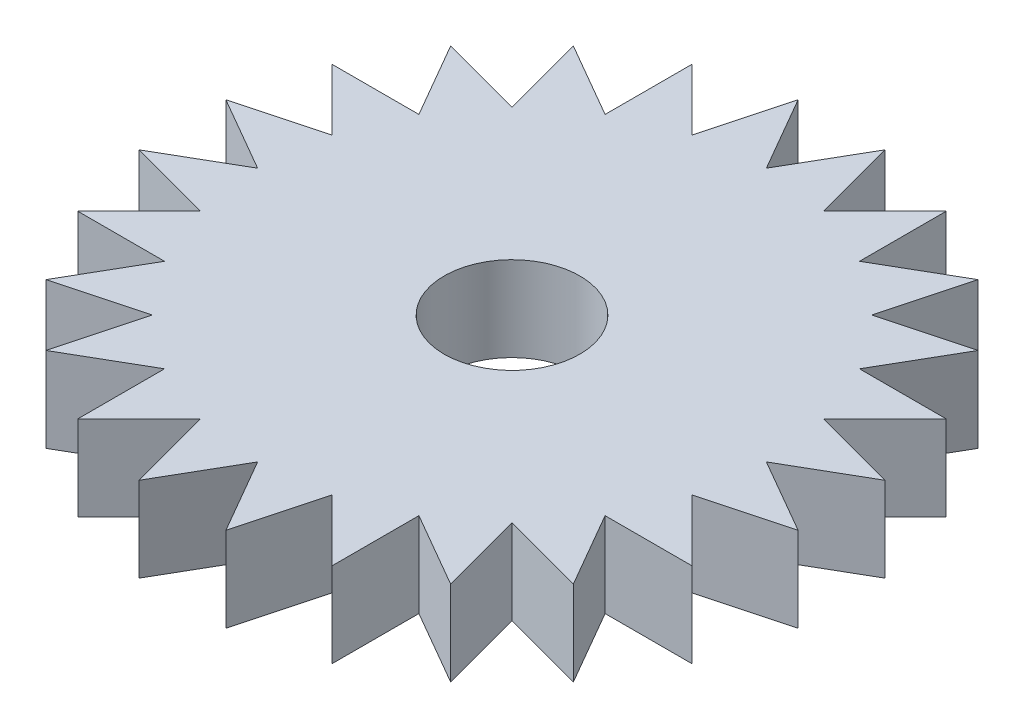
SolidWorks part; units mm, degrees
ref_plane "Front Plane" through (0, 0, 0) normal (0, 0, 1) x (1, 0, 0)
ref_plane "Top Plane" through (0, 0, 0) normal (0, 1, 0) x (1, 0, 0)
ref_plane "Right Plane" through (0, 0, 0) normal (1, 0, 0) x (0, 0, -1)
sketch "Sketch2" plane through (0, 0, 0) normal (0, 1, 0) x (1, 0, 0)
  line L0 (0, 0) -> (16.4978, 9.525) construction
  line L1 (-9.525, 16.4978) -> (9.525, -16.4978) construction
  line L2 (9.525, -16.4978) -> (4.9305, -18.4009)
  line L3 (4.9305, -18.4009) -> (-4.9305, 18.4009) construction
  line L4 (-4.9305, 18.4009) -> (-7.2278, 17.4493)
  line L5 (-9.525, 16.4978) -> (-9.525, 22.9954)
  line L6 (-9.525, 22.9954) -> (-4.9305, 18.4009)
  line L7 (-9.525, 22.9954) -> (0, 0) construction
  line L8 (-9.525, 16.4978) -> (-7.2278, 17.4493)
  line L9 (-13.4704, 13.4704) -> (-11.4977, 14.9841)
  line L10 (-9.525, 16.4978) -> (-11.4977, 14.9841)
  line L11 (-15.1521, 19.7466) -> (-9.525, 16.4978)
  line L12 (-13.4704, 13.4704) -> (-15.1521, 19.7466)
  line L13 (-16.4978, 9.525) -> (-14.9841, 11.4977)
  line L14 (-13.4704, 13.4704) -> (-14.9841, 11.4977)
  line L15 (-19.7466, 15.1521) -> (-13.4704, 13.4704)
  line L16 (-16.4978, 9.525) -> (-19.7466, 15.1521)
  line L17 (-18.4009, 4.9305) -> (-17.4493, 7.2278)
  line L18 (-16.4978, 9.525) -> (-17.4493, 7.2278)
  line L19 (-22.9954, 9.525) -> (-16.4978, 9.525)
  line L20 (-18.4009, 4.9305) -> (-22.9954, 9.525)
  line L21 (-19.05, 0) -> (-18.7254, 2.4653)
  line L22 (-18.4009, 4.9305) -> (-18.7254, 2.4653)
  line L23 (-24.6771, 3.2488) -> (-18.4009, 4.9305)
  line L24 (-19.05, 0) -> (-24.6771, 3.2488)
  line L25 (-18.4009, -4.9305) -> (-18.7254, -2.4653)
  line L26 (-19.05, 0) -> (-18.7254, -2.4653)
  line L27 (-24.6771, -3.2488) -> (-19.05, 0)
  line L28 (-18.4009, -4.9305) -> (-24.6771, -3.2488)
  line L29 (-16.4978, -9.525) -> (-17.4493, -7.2278)
  line L30 (-18.4009, -4.9305) -> (-17.4493, -7.2278)
  line L31 (-22.9954, -9.525) -> (-18.4009, -4.9305)
  line L32 (-16.4978, -9.525) -> (-22.9954, -9.525)
  line L33 (-13.4704, -13.4704) -> (-14.9841, -11.4977)
  line L34 (-16.4978, -9.525) -> (-14.9841, -11.4977)
  line L35 (-19.7466, -15.1521) -> (-16.4978, -9.525)
  line L36 (-13.4704, -13.4704) -> (-19.7466, -15.1521)
  line L37 (-9.525, -16.4978) -> (-11.4977, -14.9841)
  line L38 (-13.4704, -13.4704) -> (-11.4977, -14.9841)
  line L39 (-15.1521, -19.7466) -> (-13.4704, -13.4704)
  line L40 (-9.525, -16.4978) -> (-15.1521, -19.7466)
  line L41 (-4.9305, -18.4009) -> (-7.2278, -17.4493)
  line L42 (-9.525, -16.4978) -> (-7.2278, -17.4493)
  line L43 (-9.525, -22.9954) -> (-9.525, -16.4978)
  line L44 (-4.9305, -18.4009) -> (-9.525, -22.9954)
  line L45 (0, -19.05) -> (-2.4653, -18.7254)
  line L46 (-4.9305, -18.4009) -> (-2.4653, -18.7254)
  line L47 (-3.2488, -24.6771) -> (-4.9305, -18.4009)
  line L48 (0, -19.05) -> (-3.2488, -24.6771)
  line L49 (4.9305, -18.4009) -> (2.4653, -18.7254)
  line L50 (0, -19.05) -> (2.4653, -18.7254)
  line L51 (3.2488, -24.6771) -> (0, -19.05)
  line L52 (4.9305, -18.4009) -> (3.2488, -24.6771)
  line L53 (9.525, -16.4978) -> (7.2278, -17.4493)
  line L54 (4.9305, -18.4009) -> (7.2278, -17.4493)
  line L55 (9.525, -22.9954) -> (4.9305, -18.4009)
  line L56 (9.525, -16.4978) -> (9.525, -22.9954)
  line L57 (13.4704, -13.4704) -> (11.4977, -14.9841)
  line L58 (9.525, -16.4978) -> (11.4977, -14.9841)
  line L59 (15.1521, -19.7466) -> (9.525, -16.4978)
  line L60 (13.4704, -13.4704) -> (15.1521, -19.7466)
  line L61 (16.4978, -9.525) -> (14.9841, -11.4977)
  line L62 (13.4704, -13.4704) -> (14.9841, -11.4977)
  line L63 (19.7466, -15.1521) -> (13.4704, -13.4704)
  line L64 (16.4978, -9.525) -> (19.7466, -15.1521)
  line L65 (18.4009, -4.9305) -> (17.4493, -7.2278)
  line L66 (16.4978, -9.525) -> (17.4493, -7.2278)
  line L67 (22.9954, -9.525) -> (16.4978, -9.525)
  line L68 (18.4009, -4.9305) -> (22.9954, -9.525)
  line L69 (19.05, 0) -> (18.7254, -2.4653)
  line L70 (18.4009, -4.9305) -> (18.7254, -2.4653)
  line L71 (24.6771, -3.2488) -> (18.4009, -4.9305)
  line L72 (19.05, 0) -> (24.6771, -3.2488)
  line L73 (18.4009, 4.9305) -> (18.7254, 2.4653)
  line L74 (19.05, 0) -> (18.7254, 2.4653)
  line L75 (24.6771, 3.2488) -> (19.05, 0)
  line L76 (18.4009, 4.9305) -> (24.6771, 3.2488)
  line L77 (16.4978, 9.525) -> (17.4493, 7.2278)
  line L78 (18.4009, 4.9305) -> (17.4493, 7.2278)
  line L79 (22.9954, 9.525) -> (18.4009, 4.9305)
  line L80 (16.4978, 9.525) -> (22.9954, 9.525)
  line L81 (13.4704, 13.4704) -> (14.9841, 11.4977)
  line L82 (16.4978, 9.525) -> (14.9841, 11.4977)
  line L83 (19.7466, 15.1521) -> (16.4978, 9.525)
  line L84 (13.4704, 13.4704) -> (19.7466, 15.1521)
  line L85 (9.525, 16.4978) -> (11.4977, 14.9841)
  line L86 (13.4704, 13.4704) -> (11.4977, 14.9841)
  line L87 (15.1521, 19.7466) -> (13.4704, 13.4704)
  line L88 (9.525, 16.4978) -> (15.1521, 19.7466)
  line L89 (4.9305, 18.4009) -> (7.2278, 17.4493)
  line L90 (9.525, 16.4978) -> (7.2278, 17.4493)
  line L91 (9.525, 22.9954) -> (9.525, 16.4978)
  line L92 (4.9305, 18.4009) -> (9.525, 22.9954)
  line L93 (0, 19.05) -> (2.4653, 18.7254)
  line L94 (4.9305, 18.4009) -> (2.4653, 18.7254)
  line L95 (3.2488, 24.6771) -> (4.9305, 18.4009)
  line L96 (0, 19.05) -> (3.2488, 24.6771)
  line L97 (-4.9305, 18.4009) -> (-2.4653, 18.7254)
  line L98 (0, 19.05) -> (-2.4653, 18.7254)
  line L99 (-3.2488, 24.6771) -> (0, 19.05)
  line L100 (-4.9305, 18.4009) -> (-3.2488, 24.6771)
  circle A0 centre (0, 0) radius 19.05
  point P6 (-7.2278, 17.4493)
  point P11 (-13.3207, 35.1368)
  point P106 (0, 0)
  dimension "D1" = 38.1
  dimension "D2" = 15
  dimension "D3" = 24
  dimension "D4" = 45
  dimension "D5" = 45
  dimension "D6" = 4.5945
  dimension "D7" = 6.003
extrude "Boss-Extrude1" add sketch "Sketch2" along normal blind 6.35 contours A0 L6 L5 | A0 L15 L16 | A0 L19 L20 | A0 L11 L12 | A0 L23 L24 | A0 L27 L28 | A0 L31 L32 | A0 L39 L40 | A0 L43 L44 | A0 L47 L48 | A0 L51 L52 | A0 L55 L56 | A0 L59 L60 | A0 L63 L64 | A0 L67 L68 | A0 L71 L72 | A0 L75 L76 | A0 L79 L80 | A0 L83 L84 | A0 L87 L88 | A0 L91 L92 | A0 L95 L96 | A0 L99 L100 | L36 L35 L34 L33
sketch "Sketch3" plane through (0, 6.35, 0) normal (0, 1, 0) x (1, 0, 0)
  line L0 (-13.4704, 13.4704) -> (9.525, 16.4978)
  line L1 (9.525, 16.4978) -> (13.4704, -13.4704)
  line L2 (13.4704, -13.4704) -> (-9.525, -16.4978)
  line L3 (-9.525, -16.4978) -> (-13.4704, 13.4704)
  line L4 (-13.4704, 13.4704) -> (13.4704, -13.4704) construction
  line L5 (9.525, 16.4978) -> (-9.525, -16.4978) construction
  line L6 (-11.4977, -1.5137) -> (11.4977, 1.5137) construction
  line L7 (11.4977, 1.5137) -> (1.9727, -14.9841) construction
  line L8 (1.9727, -14.9841) -> (-11.4977, -1.5137) construction
  line L9 (-11.4977, -1.5137) -> (-1.9727, 14.9841) construction
  line L10 (-1.9727, 14.9841) -> (11.4977, 1.5137) construction
  circle A4 centre (0, 0) radius 5.08
  dimension "D1" = 10.16
extrude "Cut-Extrude3" cut sketch "Sketch3" against normal blind 6.35 contours A4
